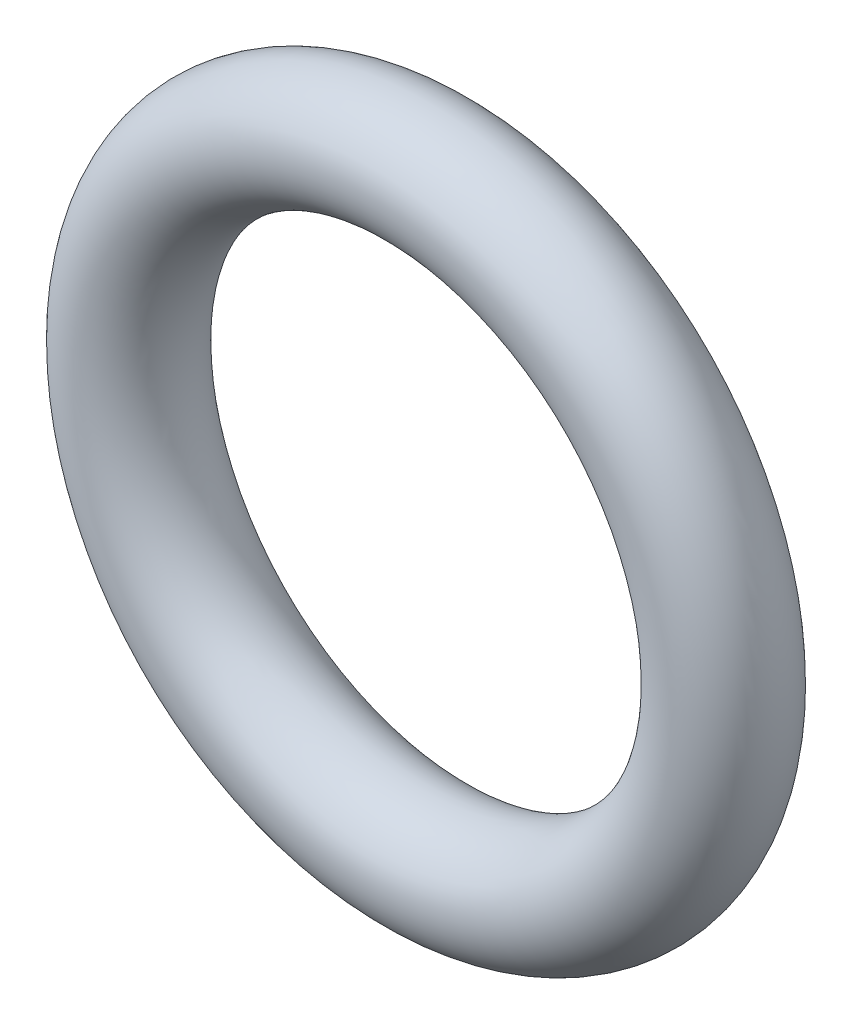
SolidWorks part; units mm, degrees
ref_plane "Front" through (0, 0, 0) normal (0, 0, 1) x (1, 0, 0)
ref_plane "Top" through (0, 0, 0) normal (0, 1, 0) x (1, 0, 0)
ref_plane "Right" through (0, 0, 0) normal (1, 0, 0) x (0, 0, -1)
sketch "Sketch1" plane through (0, 0, 0) normal (1, 0, 0) x (0, -1, 0)
  line L0 (0, -1.3081) -> (0, 1.3081) construction
  line L2 (-8.8011, 0) -> (8.8011, 0) construction
  line L3 (-5.3848, 0) -> (5.3848, 0) construction
  circle A0 centre (6.6929, 0) radius 1.3081
  point P9 (5.3848, 0)
  point P10 (8.001, 0)
  point P13 (6.6929, 1.3081)
  point P14 (6.6929, -1.3081)
  dimension "Width" = 2.6162
  dimension "ID" = 10.7696
revolve "Revolve1" add sketch "Sketch1" angle 360 about L0
